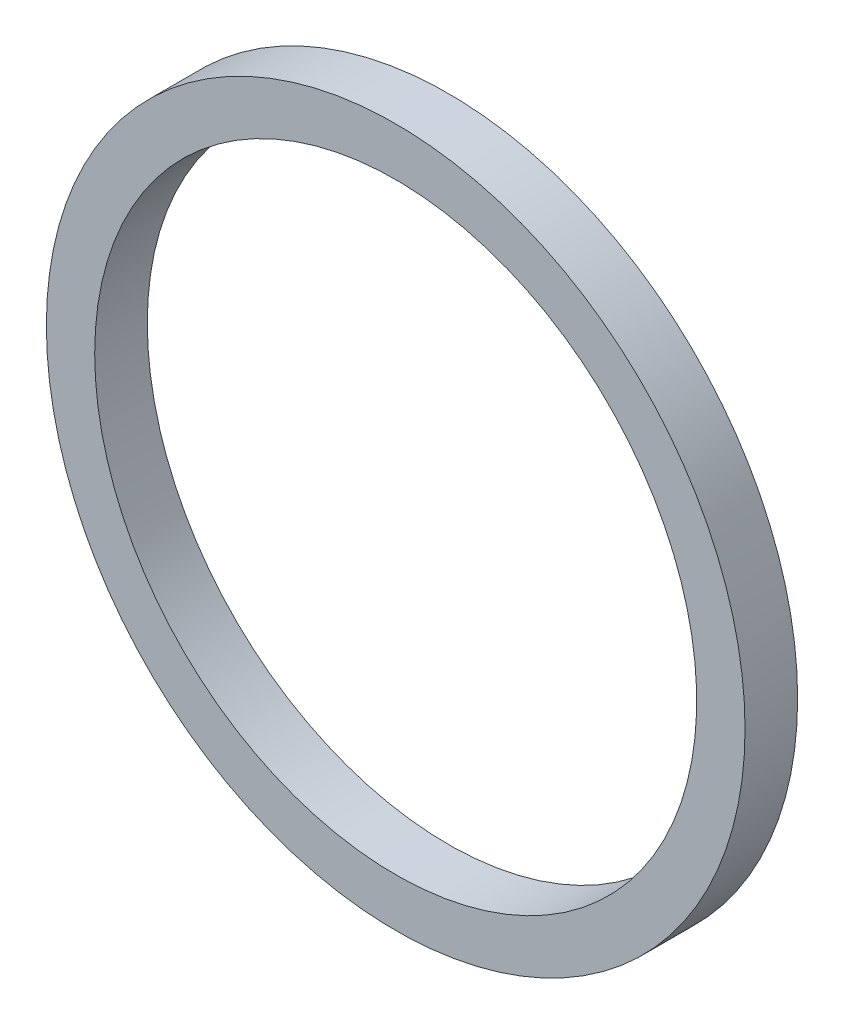
SolidWorks part; units mm, degrees
ref_plane "Front" through (0, 0, 0) normal (0, 0, 1) x (1, 0, 0)
ref_plane "Top" through (0, 0, 0) normal (0, 1, 0) x (1, 0, 0)
ref_plane "Right" through (0, 0, 0) normal (1, 0, 0) x (0, 0, -1)
sketch "Sketch1" plane through (0, 0, 0) normal (0, 0, 1) x (1, 0, 0)
  circle A0 centre (0, 0) radius 19
  circle A1 centre (0, 0) radius 22.05
  dimension "D1" = 44.1
  dimension "D2" = 38
extrude "Boss-Extrude1" add sketch "Sketch1" along normal blind 3.32
